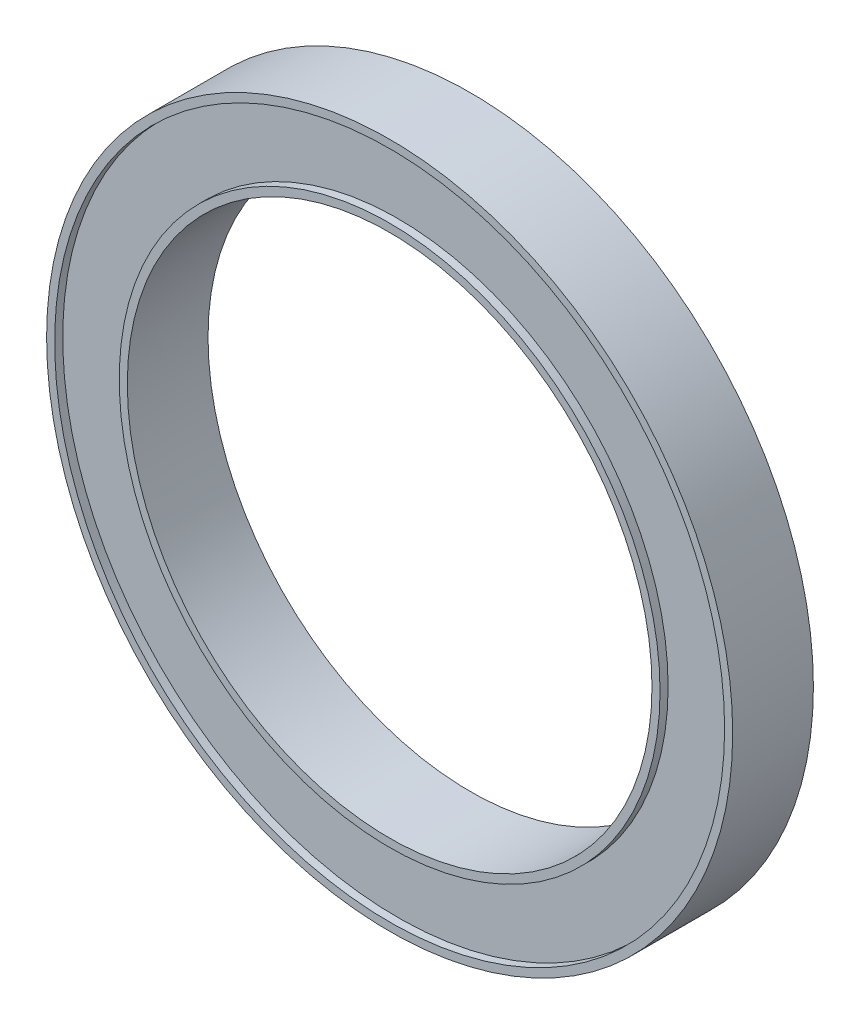
SolidWorks part; units mm, degrees
ref_plane "Front Plane" through (0, 0, 0) normal (0, 0, 1) x (1, 0, 0)
ref_plane "Top Plane" through (0, 0, 0) normal (0, 1, 0) x (1, 0, 0)
ref_plane "Right Plane" through (0, 0, 0) normal (1, 0, 0) x (0, 0, -1)
sketch "Sketch1" plane through (0, 0, 0) normal (0, 0, 1) x (1, 0, 0)
  circle A0 centre (0, 0) radius 42.5
  circle A1 centre (0, 0) radius 32.5
  dimension "D1" = 65
  dimension "D2" = 85
extrude "Boss-Extrude1" add sketch "Sketch1" along normal mid plane 10
sketch "Sketch2" plane through (0, 0, 5) normal (0, 0, 1) x (1, 0, 0)
  circle A2 centre (0, 0) radius 33.5
  circle A3 centre (0, 0) radius 33.5
  circle A5 centre (0, 0) radius 41.5
  circle A6 centre (0, 0) radius 41.5
  dimension "D1" = 1
  dimension "D2" = 1
extrude "Cut-Extrude1" cut sketch "Sketch2" against normal blind 1
mirror "Mirror1" about plane through (0, 0, 0) normal (0, 0, 1) of "Cut-Extrude1"
